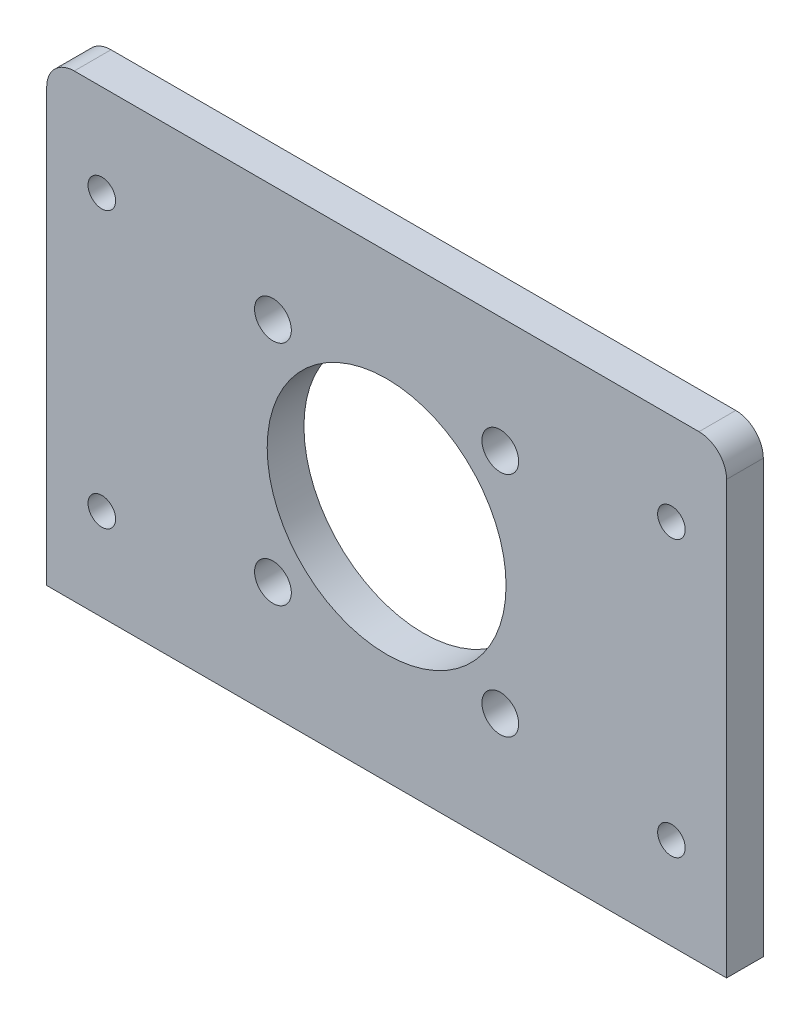
SolidWorks part; units mm, degrees
material "A-玻璃纤维"
ref_plane "前视基准面" through (0, 0, 0) normal (0, 0, 1) x (1, 0, 0)
ref_plane "上视基准面" through (0, 0, 0) normal (0, 1, 0) x (1, 0, 0)
ref_plane "右视基准面" through (0, 0, 0) normal (1, 0, 0) x (0, 0, -1)
sketch "草图1" plane through (0, 0, 0) normal (0, 0, 1) x (1, 0, 0)
  line L1 (-37, -25) -> (37, -25)
  line L2 (-37, -25) -> (-37, 25)
  line L3 (-37, 25) -> (37, 25)
  line L4 (37, -25) -> (37, 25)
  line L5 (-37, -25) -> (37, 25) construction
  line L6 (-37, 25) -> (37, -25) construction
  point P0 (0, 0)
  dimension "D1" = 74
  dimension "D2" = 50
extrude "凸台-拉伸1" add sketch "草图1" along normal blind 4
sketch "草图2" plane through (0, 0, 4) normal (0, 0, 1) x (1, 0, 0)
  circle A0 centre (0, 0) radius 13
  dimension "D1" = 26
extrude "切除-拉伸1" cut sketch "草图2" against normal through all
sketch "草图3" plane through (0, 0, 4) normal (0, 0, 1) x (1, 0, 0)
  line L1 (-12.3744, -12.3744) -> (12.3744, -12.3744)
  line L2 (-12.3744, -12.3744) -> (-12.3744, 12.3744)
  line L3 (-12.3744, 12.3744) -> (12.3744, 12.3744)
  line L4 (12.3744, -12.3744) -> (12.3744, 12.3744)
  line L5 (-12.3744, -12.3744) -> (12.3744, 12.3744) construction
  line L6 (-12.3744, 12.3744) -> (12.3744, -12.3744) construction
  circle A0 centre (12.3744, 12.3744) radius 2
  point P0 (0, 0)
  dimension "D1" = 4
  dimension "D2" = 35
  dimension "D3" = 45
extrude "切除-拉伸2" cut sketch "草图3" against normal through all contours L4 A0 L3 | L3 A0 L4
mirror "镜向1" about plane through (0, 0, 0) normal (1, 0, 0) of "切除-拉伸2"
mirror "镜向2" about plane through (0, 0, 0) normal (0, 1, 0) of "镜向1", "切除-拉伸2"
sketch "草图4" plane through (0, 0, 4) normal (0, 0, 1) x (1, 0, 0)
  line L0 (-37, 25) -> (-37, -25) construction
  line L1 (31, -15) -> (-31, -15)
  line L2 (31, -15) -> (31, 15)
  line L3 (31, 15) -> (-31, 15)
  line L4 (-31, -15) -> (-31, 15)
  line L5 (31, -15) -> (-31, 15) construction
  line L6 (31, 15) -> (-31, -15) construction
  circle A0 centre (-31, 15) radius 1.5
  point P0 (0, 0)
  dimension "D1" = 3
  dimension "D2" = 15
  dimension "D3" = 6
extrude "切除-拉伸3" cut sketch "草图4" against normal through all contours L4 A0 L3 | L3 A0 L4
mirror "镜向3" about plane through (0, 0, 0) normal (1, 0, 0) of "切除-拉伸3"
mirror "镜向4" about plane through (0, 0, 0) normal (0, 1, 0) of "镜向3", "切除-拉伸3"
fillet "圆角2" radius 3 2 edges at (37, 25, 2) (-37, 25, 2)
